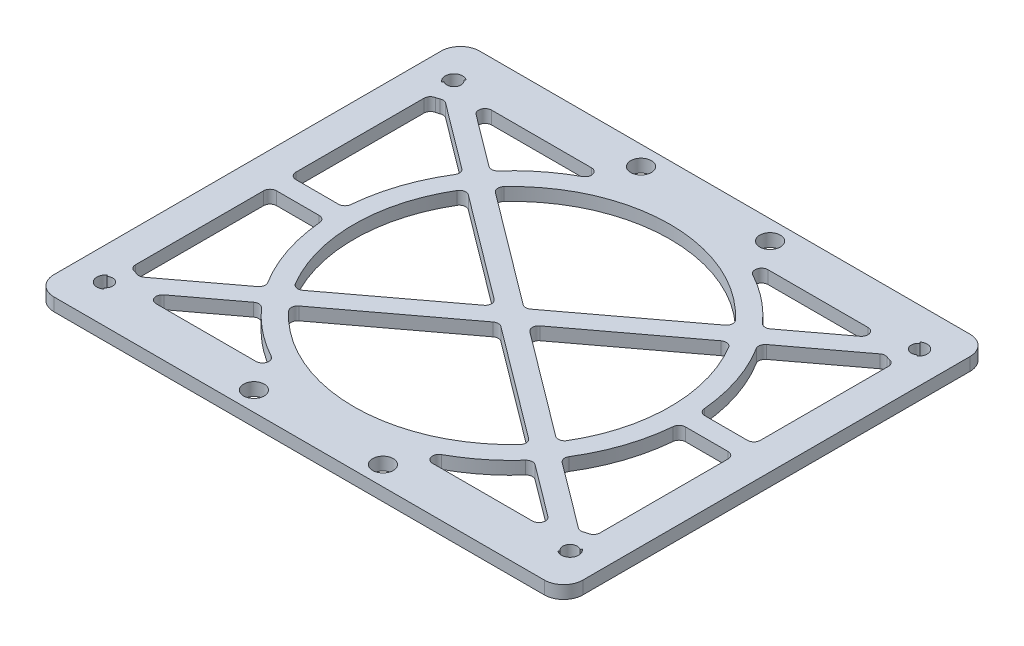
SolidWorks part; units mm, degrees
material "Thornel Mat VMA"
ref_plane "前视基准面" through (0, 0, 0) normal (0, 0, 1) x (1, 0, 0)
ref_plane "上视基准面" through (0, 0, 0) normal (0, 1, 0) x (1, 0, 0)
ref_plane "右视基准面" through (0, 0, 0) normal (1, 0, 0) x (0, 0, -1)
other "Configuration Table"
sketch "草图1" plane through (0, 0, 0) normal (0, 1, 0) x (1, 0, 0)
  line L1 (-10, 30) -> (10, 30) construction
  line L2 (-10, 30) -> (-10, -30) construction
  line L3 (-10, -30) -> (10, -30) construction
  line L4 (10, 30) -> (10, -30) construction
  line L5 (-10, 30) -> (10, -30) construction
  line L6 (-10, -30) -> (10, 30) construction
  line L7 (-36, 27) -> (36, 27) construction
  line L8 (-36, 27) -> (-36, -27) construction
  line L9 (-36, -27) -> (36, -27) construction
  line L10 (36, 27) -> (36, -27) construction
  line L11 (-36, 27) -> (36, -27) construction
  line L12 (-36, -27) -> (36, 27) construction
  line L13 (-41, 33) -> (41, 33)
  line L14 (-41, 33) -> (-41, -33)
  line L15 (-41, -33) -> (41, -33)
  line L16 (41, 33) -> (41, -33)
  line L17 (-41, 33) -> (41, -33) construction
  line L18 (-41, -33) -> (41, 33) construction
  circle A0 centre (10, -30) radius 1.6
  circle A1 centre (-10, -30) radius 1.6
  circle A2 centre (-10, 30) radius 1.6
  circle A3 centre (10, 30) radius 1.6
  circle A4 centre (36, -27) radius 1.35
  circle A5 centre (36, 27) radius 1.35
  circle A6 centre (-36, 27) radius 1.35
  circle A7 centre (-36, -27) radius 1.35
  point P0 (0, 0)
  point P10 (0, 0)
  point P19 (0, 0)
  dimension "D5" = 2.7
  dimension "D8" = 3.2
  dimension "D1" = 60
  dimension "D2" = 20
  dimension "D3" = 54
  dimension "D4" = 72
  dimension "D6" = 3
  dimension "D7" = 5
extrude "凸台-拉伸1" add sketch "草图1" along normal blind 2
fillet "圆角1" radius 3 4 edges at (-41, 1, 33) (-41, 1, -33) (41, 1, -33) (41, 1, 33)
sketch "草图2" plane through (0, 2, 0) normal (0, 1, 0) x (1, 0, 0)
  line L0 (-36, -27) -> (36, 27) construction
  line L1 (36, -27) -> (-36, 27) construction
  line L2 (41, -30) -> (41, 30) construction
  line L3 (-36, 26) -> (36, 26)
  line L4 (-36, 26) -> (-36, -26)
  line L5 (-36, -26) -> (36, -26)
  line L6 (36, 26) -> (36, -26)
  line L7 (-41, 30) -> (-41, -30) construction
  circle A1 centre (10, 30) radius 1.6 construction
  circle A2 centre (-36, -27) radius 3.75
  circle A3 centre (36, -27) radius 3.75
  circle A4 centre (36, 27) radius 3.75
  circle A5 centre (-36, 27) radius 3.75
  circle A6 centre (10, -30) radius 1.6 construction
  dimension "D5" = 7.5
  dimension "D1" = 5
  dimension "D2" = 4
  dimension "D3" = 4
  dimension "D4" = 5
extrude "切除-拉伸1" cut sketch "草图2" against normal blind 10 contours A5 L4 A2 L5 A3 L6 A4 L3
sketch "草图3" plane through (0, 2, 0) normal (0, 1, 0) x (1, 0, 0)
  line L0 (36, -27) -> (-36, 27)
  line L1 (-36, -27) -> (36, 27)
  line L5 (-36, 0) -> (-26, 0)
  line L6 (-36, 23.25) -> (-36, -23.25) construction
  line L7 (36, -23.25) -> (36, 23.25) construction
  line L8 (26, 0) -> (36, 0)
  circle A0 centre (0, 0) radius 26
  dimension "D1" = 52
extrude "拉伸-薄壁1" add sketch "草图3" against normal blind 2 thin thin type mid plane wall 3
sketch "草图4" plane through (0, 2, 0) normal (0, 1, 0) x (1, 0, 0)
  line L0 (-35.19, -28.08) -> (-36.81, -25.92) construction
  line L4 (35.1, 28.2) -> (36.9, 25.8) construction
  line L6 (36.9, -25.8) -> (35.1, -28.2) construction
  circle A5 centre (36, 27) radius 1.1
  circle A6 centre (-36, 27) radius 1.1
  circle A7 centre (-36, -27) radius 1.1
  circle A8 centre (36, -27) radius 1.1
  dimension "D1" = 2.2
extrude "切除-拉伸2" cut sketch "草图4" against normal blind 2
fillet "圆角2" radius 1 44 edges at (-20.4632, 1, -13.4724) (18.6632, 1, 15.8724) (-20.4632, 1, 13.4724) (18.6632, 1, -15.8724) (-2.5, 1, 0) (-18.6632, 1, 15.8724) (20.4632, 1, -13.4724) (-18.6632, 1, -15.8724) (20.4632, 1, 13.4724) (0, 1, -1.875) (2.5, 1, 0) (-22.8672, 1, 15.2754) (21.0672, 1, -17.6754) (32.1667, 1, -26) (8.9582, 1, -26) (-8.9582, 1, -26) (-36, 1, -1.5) (-27.4591, 1, -1.5) (21.0672, 1, 17.6754) (-22.8672, 1, -15.2754) (-21.0672, 1, 17.6754) (22.8672, 1, -15.2754) (27.4591, 1, -1.5) (36, 1, -1.5) (8.9582, 1, 26) (-8.9582, 1, 26) (-32.1667, 1, 26) (-27.4591, 1, 1.5) (-36, 1, 1.5) (-21.0672, 1, -17.6754) (22.8672, 1, 15.2754) (-32.1667, 1, -26) (32.1667, 1, 26) (36, 1, 1.5) (27.4591, 1, 1.5) (0, 1, 1.875) (-36, 1, -23.25) (-34.1505, 1, -23.7378) (36, 1, -23.25) (34.1505, 1, -23.7378) (-34.1505, 1, 23.7378) (36, 1, 23.25) (34.1505, 1, 23.7378) (-36, 1, 23.25)
